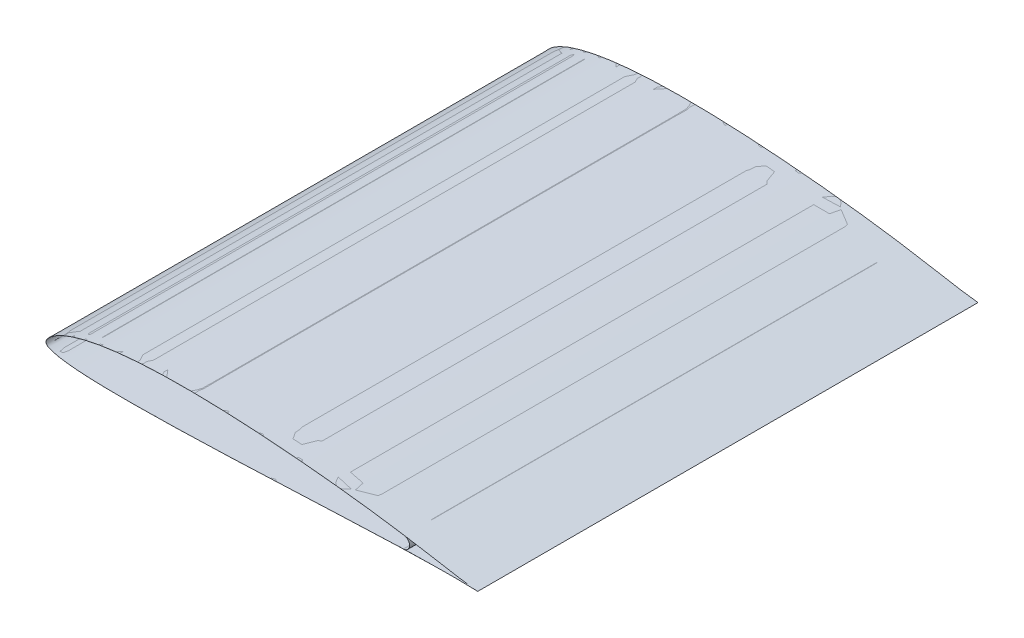
SolidWorks part; units mm, degrees
ref_plane "Front Plane" through (0, 0, 0) normal (0, 0, 1) x (1, 0, 0)
ref_plane "Top Plane" through (0, 0, 0) normal (0, 1, 0) x (1, 0, 0)
ref_plane "Right Plane" through (0, 0, 0) normal (1, 0, 0) x (0, 0, -1)
curve "Curve1"
  spline degree 3 poles (152.4, 0, 0) (152.2328, 0.0185, 0) (151.5718, 0.0917, 0) (150.114, 0.2839, 0) (147.7494, 0.6387, 0) (144.5559, 1.1702, 0) (140.6154, 1.8591, 0) (136.0078, 2.6715, 0) (130.8064, 3.5628, 0) (125.0738, 4.4862, 0) (118.8647, 5.3978, 0) (112.2333, 6.273, 0) (105.2435, 7.1061, 0) (97.9697, 7.8893, 0) (90.4927, 8.6067, 0) (82.8953, 9.2407, 0) (75.2587, 9.7775, 0) (67.6629, 10.1988, 0) (60.1868, 10.4917, 0) (52.9059, 10.6451, 0) (45.8917, 10.6446, 0) (39.2107, 10.4862, 0) (32.9233, 10.1644, 0) (27.0837, 9.6709, 0) (21.7372, 9.0165, 0) (16.9243, 8.2041, 0) (12.6763, 7.2498, 0) (9.0198, 6.1745, 0) (5.9657, 5.002, 0) (3.544, 3.7699, 0) (1.7048, 2.5315, 0) (0.5752, 1.3447, 0) (-0.1707, 0.2031, 0) (0.3376, -1.0018, 0) (1.7929, -1.5467, 0) (3.7942, -2.1772, 0) (6.6434, -2.6439, 0) (10.2161, -3.042, 0) (14.5301, -3.3199, 0) (19.534, -3.4977, 0) (25.1869, -3.5776, 0) (31.4286, -3.5738, 0) (38.1919, -3.4966, 0) (45.4016, -3.3493, 0) (52.9784, -3.1418, 0) (60.8387, -2.8853, 0) (68.895, -2.5879, 0) (77.0574, -2.2589, 0) (85.235, -1.9077, 0) (93.3354, -1.5502, 0) (101.266, -1.1955, 0) (108.9342, -0.8624, 0) (116.2465, -0.5575, 0) (123.1102, -0.3069, 0) (129.4317, -0.1079, 0) (135.1235, 0.028, 0) (140.1036, 0.1089, 0) (144.2994, 0.1399, 0) (147.6448, 0.1242, 0) (150.0834, 0.0865, 0) (151.3998, 0.0403, 0) (151.8986, 0.0229, 0) knots 0 0 0 0 0.001635 0.006466 0.014297 0.024884 0.037944 0.053194 0.070377 0.089257 0.109652 0.131396 0.154295 0.178097 0.202531 0.227329 0.252226 0.276966 0.301297 0.324972 0.347773 0.369494 0.389947 0.408979 0.426466 0.442307 0.456421 0.468774 0.479345 0.488156 0.495223 0.500608 0.504417 0.507344 0.511893 0.518766 0.528062 0.53975 0.553782 0.570059 0.588441 0.608748 0.63075 0.654208 0.678865 0.704451 0.730678 0.757254 0.783883 0.810266 0.836095 0.861073 0.884897 0.907258 0.927856 0.946395 0.962618 0.976286 0.987193 0.995147 1 1 1 1
sketch "Sketch1" plane through (0, 0, 0) normal (0, 0, 1) x (1, 0, 0)
  line L0 (151.8986, 0.0229) -> (152.4, 0)
  line L1 (151.8975, -0.0089) -> (153.3791, -0.0764)
  line L2 (127, 1.9788) -> (127, -0.1865) construction
  line L3 (0, 0) -> (0, 1.9788) construction
  line L4 (127, 1.9788) -> (0, 1.9788) construction
  arc A0 (127, -0.1865) -> (127.3401, 4.1173) centre (127, 1.9788) ccw
  spline S0 degree 3 poles (-120.0863, -2986.5223) (204.7313, 14.3063) (176.6016, -3.2082) (150.114, 0.2839) (147.7494, 0.6387) (144.5559, 1.1702) (140.6154, 1.8591) (136.0078, 2.6715) (130.8064, 3.5628) (125.0738, 4.4862) (118.8647, 5.3978) (112.2333, 6.273) (105.2435, 7.1061) (97.9697, 7.8893) (90.4927, 8.6067) (82.8953, 9.2407) (75.2587, 9.7775) (67.6629, 10.1988) (60.1868, 10.4917) (52.9059, 10.6451) (45.8917, 10.6446) (39.2107, 10.4862) (32.9233, 10.1644) (27.0837, 9.6709) (21.7372, 9.0165) (16.9243, 8.2041) (12.6763, 7.2498) (9.0198, 6.1745) (5.9657, 5.002) (3.544, 3.7699) (1.7048, 2.5315) (0.5752, 1.3447) (-0.1707, 0.2031) (0.3376, -1.0018) (1.7929, -1.5467) (3.7942, -2.1772) (6.6434, -2.6439) (10.2161, -3.042) (14.5301, -3.3199) (19.534, -3.4977) (25.1869, -3.5776) (31.4286, -3.5738) (38.1919, -3.4966) (45.4016, -3.3493) (52.9784, -3.1418) (60.8387, -2.8853) (68.895, -2.5879) (77.0574, -2.2589) (85.235, -1.9077) (93.3354, -1.5502) (101.266, -1.1955) (108.9342, -0.8624) (116.2465, -0.5575) (123.1102, -0.3069) (129.4317, -0.1079) (135.1235, 0.028) (140.1036, 0.1089) (144.2994, 0.1399) (147.6448, 0.1242) (196.5916, -0.6332) (243.4783, -35.3543) (374.0575, 2989.6631) knots -0.245458 -0.245458 -0.245458 -0.245458 0.001635 0.006466 0.014297 0.024884 0.037944 0.053194 0.070377 0.089257 0.109652 0.131396 0.154295 0.178097 0.202531 0.227329 0.252226 0.276966 0.301297 0.324972 0.347773 0.369494 0.389947 0.408979 0.426466 0.442307 0.456421 0.468774 0.479345 0.488156 0.495223 0.500608 0.504417 0.507344 0.511893 0.518766 0.528062 0.53975 0.553782 0.570059 0.588441 0.608748 0.63075 0.654208 0.678865 0.704451 0.730678 0.757254 0.783883 0.810266 0.836095 0.861073 0.884897 0.907258 0.927856 0.946395 0.962618 0.976286 0.987193 0.995147 1.45225 1.45225 1.45225 1.45225 only from (152.4, 0) to (151.8986, 0.0229) construction
  spline S1 degree 3 poles (152.4, 0) (152.2328, 0.0185) (151.5718, 0.0917) (150.114, 0.2839) (147.7494, 0.6387) (144.5559, 1.1702) (140.6154, 1.8591) (136.0078, 2.6715) (130.8064, 3.5628) (125.0738, 4.4862) (118.8647, 5.3978) (112.2333, 6.273) (105.2435, 7.1061) (97.9697, 7.8893) (90.4927, 8.6067) (82.8953, 9.2407) (75.2587, 9.7775) (67.6629, 10.1988) (60.1868, 10.4917) (52.9059, 10.6451) (45.8917, 10.6446) (39.2107, 10.4862) (32.9233, 10.1644) (27.0837, 9.6709) (21.7372, 9.0165) (16.9243, 8.2041) (12.6763, 7.2498) (9.0198, 6.1745) (5.9657, 5.002) (3.544, 3.7699) (1.7048, 2.5315) (0.5752, 1.3447) (-0.1707, 0.2031) (0.3376, -1.0018) (1.7929, -1.5467) (3.7942, -2.1772) (6.6434, -2.6439) (10.2161, -3.042) (14.5301, -3.3199) (19.534, -3.4977) (25.1869, -3.5776) (31.4286, -3.5738) (38.1919, -3.4966) (45.4016, -3.3493) (52.9784, -3.1418) (60.8387, -2.8853) (68.895, -2.5879) (77.0574, -2.2589) (85.235, -1.9077) (93.3354, -1.5502) (101.266, -1.1955) (108.9342, -0.8624) (116.2465, -0.5575) (123.1102, -0.3069) (129.4317, -0.1079) (135.1235, 0.028) (140.1036, 0.1089) (144.2994, 0.1399) (147.6448, 0.1242) (150.0834, 0.0865) (151.3998, 0.0403) (151.8986, 0.0229) knots 0 0 0 0 0.001635 0.006466 0.014297 0.024884 0.037944 0.053194 0.070377 0.089257 0.109652 0.131396 0.154295 0.178097 0.202531 0.227329 0.252226 0.276966 0.301297 0.324972 0.347773 0.369494 0.389947 0.408979 0.426466 0.442307 0.456421 0.468774 0.479345 0.488156 0.495223 0.500608 0.504417 0.507344 0.511893 0.518766 0.528062 0.53975 0.553782 0.570059 0.588441 0.608748 0.63075 0.654208 0.678865 0.704451 0.730678 0.757254 0.783883 0.810266 0.836095 0.861073 0.884897 0.907258 0.927856 0.946395 0.962618 0.976286 0.987193 0.995147 1 1 1 1
  spline S2 degree 1 poles (153.3791, -0.0764) (151.8975, -0.0089) knots 0 0 1 1 construction
  spline S3 degree 3 poles (153.3791, -0.0764) (151.7774, 0.1009) (148.5805, 0.5159) (142.2245, 1.6025) (134.2896, 3.0178) (124.7452, 4.5926) (111.9735, 6.3946) (99.1561, 7.8407) (86.3118, 9.0095) (76.6654, 9.7293) (67.0073, 10.2743) (57.3397, 10.6177) (47.666, 10.7159) (39.6051, 10.5424) (33.1643, 10.1997) (28.3418, 9.8166) (23.5326, 9.287) (18.7468, 8.5727) (14.7913, 7.7795) (11.6643, 6.9837) (9.3463, 6.2887) (7.0637, 5.4719) (5.2171, 4.6605) (3.7916, 3.904) (2.7465, 3.2736) (1.7584, 2.5606) (1.0349, 1.8802) (0.5105, 1.2522) (0.1284, 0.7273) (-0.0881, 0.1431) (0.0691, -0.4961) (0.4759, -0.9952) (1.0162, -1.2913) (1.6095, -1.5012) (2.3812, -1.7634) (3.338, -2.0493) (4.5134, -2.3146) (5.7112, -2.5185) (7.3145, -2.744) (9.3149, -2.9719) (11.7245, -3.1712) (14.1404, -3.3155) (17.3623, -3.4586) (21.3913, -3.5627) (26.2281, -3.6092) (31.0645, -3.6025) (37.5127, -3.541) (45.5718, -3.3827) (55.2404, -3.1069) (64.9071, -2.773) (77.7938, -2.2687) (93.8987, -1.5595) (113.2234, -0.6882) (129.3335, -0.1044) (142.2274, 0.1249) (148.6761, 0.1041) (151.8975, -0.0089) knots -0.003181 -0.003181 -0.003181 -0.003181 0.012493 0.028168 0.059518 0.090867 0.122216 0.184915 0.216265 0.247614 0.278963 0.310313 0.341662 0.373012 0.388686 0.404361 0.420036 0.435711 0.451385 0.459223 0.46706 0.474897 0.482735 0.486653 0.490572 0.494491 0.498409 0.500369 0.502328 0.504287 0.506247 0.508206 0.510165 0.512125 0.514084 0.518003 0.521921 0.52584 0.529759 0.537596 0.545433 0.553271 0.561108 0.576783 0.592458 0.608132 0.623807 0.655156 0.686506 0.717855 0.749205 0.811904 0.874602 0.937301 0.968651 1 1 1 1
  point P7 (0, 1.7455)
  dimension "D2" = 127
  dimension "D1" = 0.0318
extrude "Boss-Extrude2" add sketch "Sketch1" along normal blind 177.8 contours L0 S1 A0 | L1 S3 S1 L0 A0
